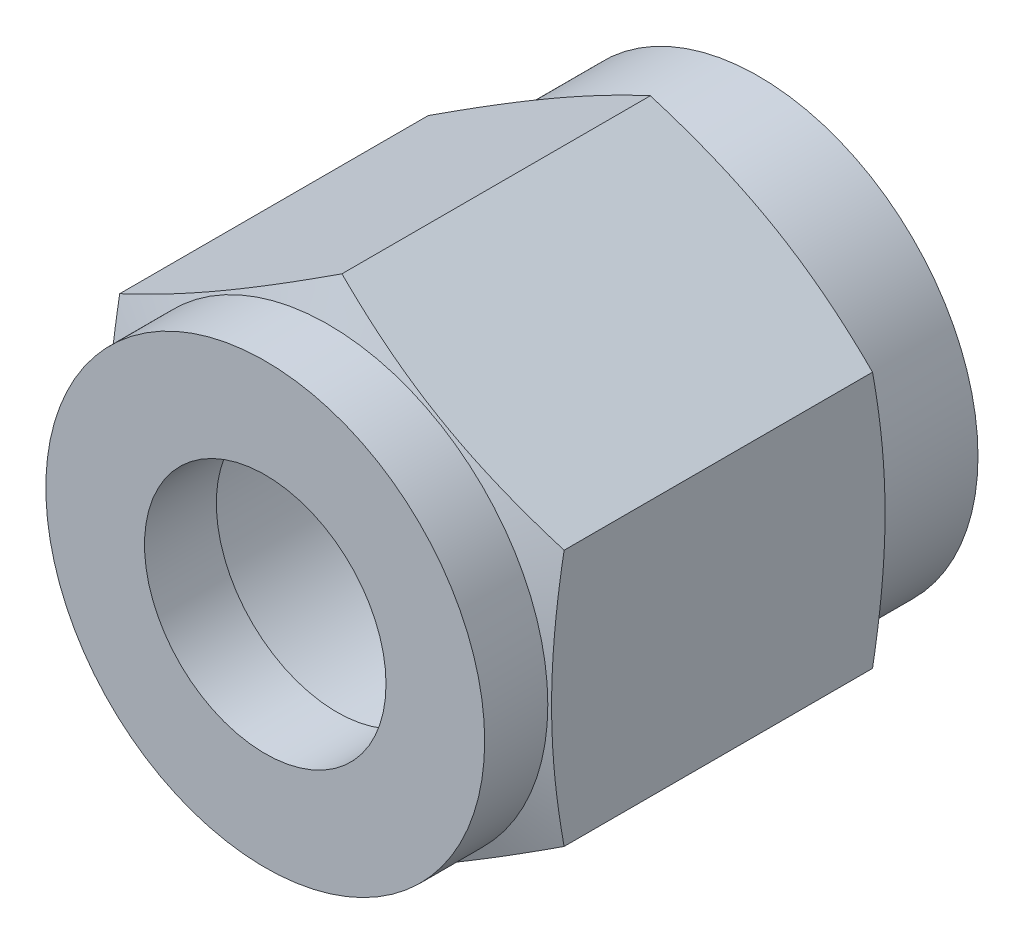
SolidWorks part; units mm, degrees
ref_plane "Front Plane" through (0, 0, 0) normal (0, 0, 1) x (1, 0, 0)
ref_plane "Top Plane" through (0, 0, 0) normal (0, 1, 0) x (1, 0, 0)
ref_plane "Right Plane" through (0, 0, 0) normal (1, 0, 0) x (0, 0, -1)
sketch "Sketch1" plane through (0, 0, 0) normal (1, 0, 0) x (0, 0, -1)
  line L0 (-13.5636, 3.8862) -> (-15.875, 3.8862)
  line L1 (-15.875, 3.8862) -> (-15.875, 7.0612)
  line L7 (-15.875, 7.0612) -> (-13.843, 7.0612)
  line L9 (-13.843, 7.0612) -> (-12.9185, 9.6012)
  line L10 (-12.9185, 9.6012) -> (-3.9725, 9.6012)
  line L11 (-3.9725, 9.6012) -> (-3.048, 7.0612)
  line L13 (-3.048, 7.0612) -> (0, 7.0612)
  line L14 (0, 7.0612) -> (0, 5.0038)
  line L15 (-13.5636, 3.8862) -> (-13.5636, 5.0038)
  line L16 (-13.5636, 5.0038) -> (0, 5.0038)
  line L17 (2.002, 0) -> (9.2467, 0) construction
  dimension "D2" = 20
  dimension "D3" = 20
  dimension "D4" = 15.875
  dimension "D5" = 2.032
  dimension "D6" = 3.048
  dimension "D12" = 2.54
  dimension "D13" = 13.5636
  dimension "D14" = 7.7724
  dimension "D15" = 10.0076
  dimension "D18" = 14.1224
revolve "Revolve1" add sketch "Sketch1" angle 360 about L17
sketch "Sketch2" plane through (0, 0, 0) normal (0, 0, 1) x (1, 0, 0)
  line L1 (0, 8.2562) -> (-7.1501, 4.1281)
  line L2 (-7.1501, 4.1281) -> (-7.1501, -4.1281)
  line L3 (-7.1501, -4.1281) -> (0, -8.2562)
  line L4 (0, -8.2562) -> (7.1501, -4.1281)
  line L5 (7.1501, -4.1281) -> (7.1501, 4.1281)
  line L6 (7.1501, 4.1281) -> (0, 8.2562)
  circle A0 centre (0, 0) radius 7.1501 construction
  dimension "D1" = 14.3002
extrude "Cut-Extrude1" cut sketch "Sketch2" along normal through all flip side to cut
